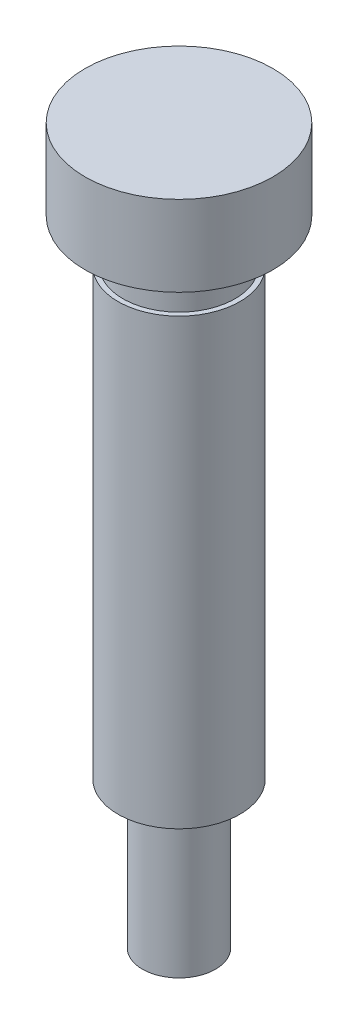
SolidWorks part; units mm, degrees
ref_plane "Front Plane" through (0, 0, 0) normal (0, 0, 1) x (1, 0, 0)
ref_plane "Top Plane" through (0, 0, 0) normal (0, 1, 0) x (1, 0, 0)
ref_plane "Right Plane" through (0, 0, 0) normal (1, 0, 0) x (0, 0, -1)
sketch "Sketch1" plane through (0, 0, 0) normal (0, 0, 1) x (1, 0, 0)
  line L0 (0, 0) -> (1.5, 0)
  line L1 (1.5, 0) -> (1.5, 6)
  line L2 (1.5, 6) -> (2.5, 6)
  line L3 (2.5, 6) -> (2.5, 24.2)
  line L4 (2.3, 24.2) -> (2.3, 26)
  line L5 (2.3, 26) -> (3.85, 26)
  line L6 (3.85, 26) -> (3.85, 29.3)
  line L7 (3.85, 29.3) -> (0, 29.3)
  line L8 (0, 29.3) -> (0, 0)
  line L9 (2.3, 24.2) -> (2.5, 24.2)
  point P10 (10.3816, 27.9376)
  point P12 (13.2002, 22.1242)
  point P13 (10.2054, 22.1242)
  dimension "D1" = 6
  dimension "D2" = 20
  dimension "D3" = 1.8
  dimension "D4" = 1.5
  dimension "D5" = 2.5
  dimension "D6" = 2.3
  dimension "D7" = 3.85
  dimension "D8" = 3.3
revolve "Revolve1" add sketch "Sketch1" angle 360 about L8
